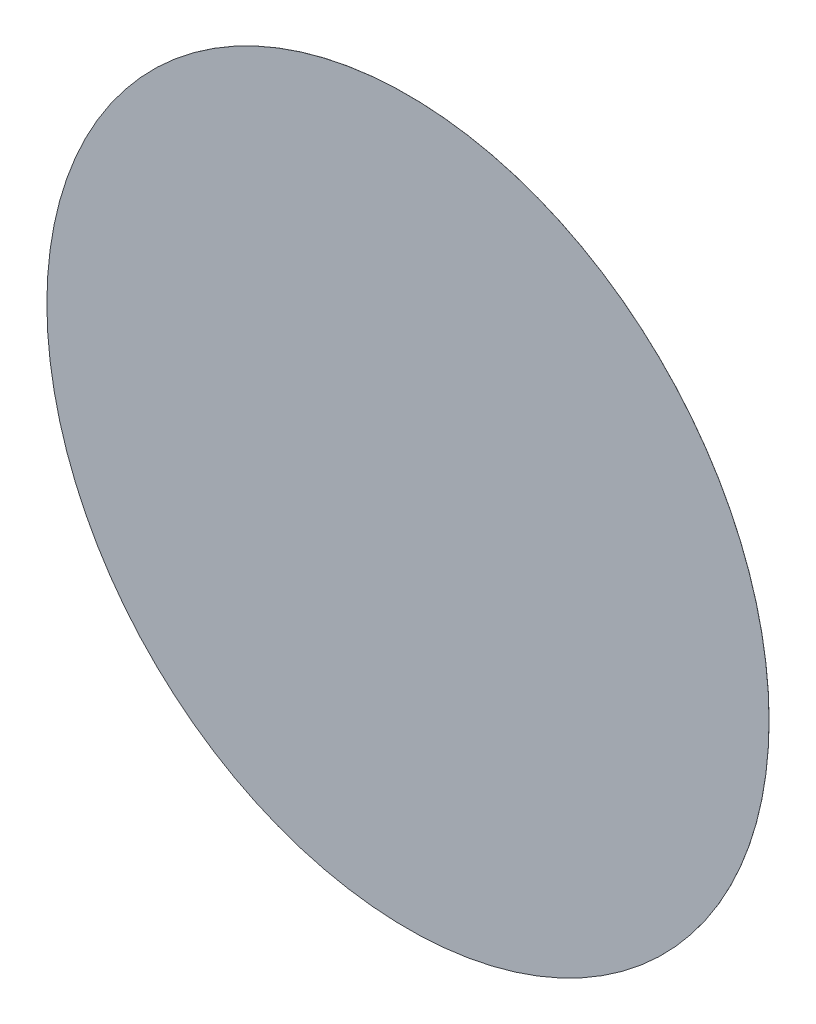
SolidWorks part; units mm, degrees
ref_plane "Front Plane" through (0, 0, 0) normal (0, 0, 1) x (1, 0, 0)
ref_plane "Top Plane" through (0, 0, 0) normal (0, 1, 0) x (1, 0, 0)
ref_plane "Right Plane" through (0, 0, 0) normal (1, 0, 0) x (0, 0, -1)
sketch "Sketch1" plane through (-127, 0, 0) normal (0, 0, 1) x (1, 0, 0)
  circle A0 centre (-78.2675, 78.6103) radius 818.8372
extrude "Boss-Extrude2" add sketch "Sketch1" along normal blind 0.15 contours A0
